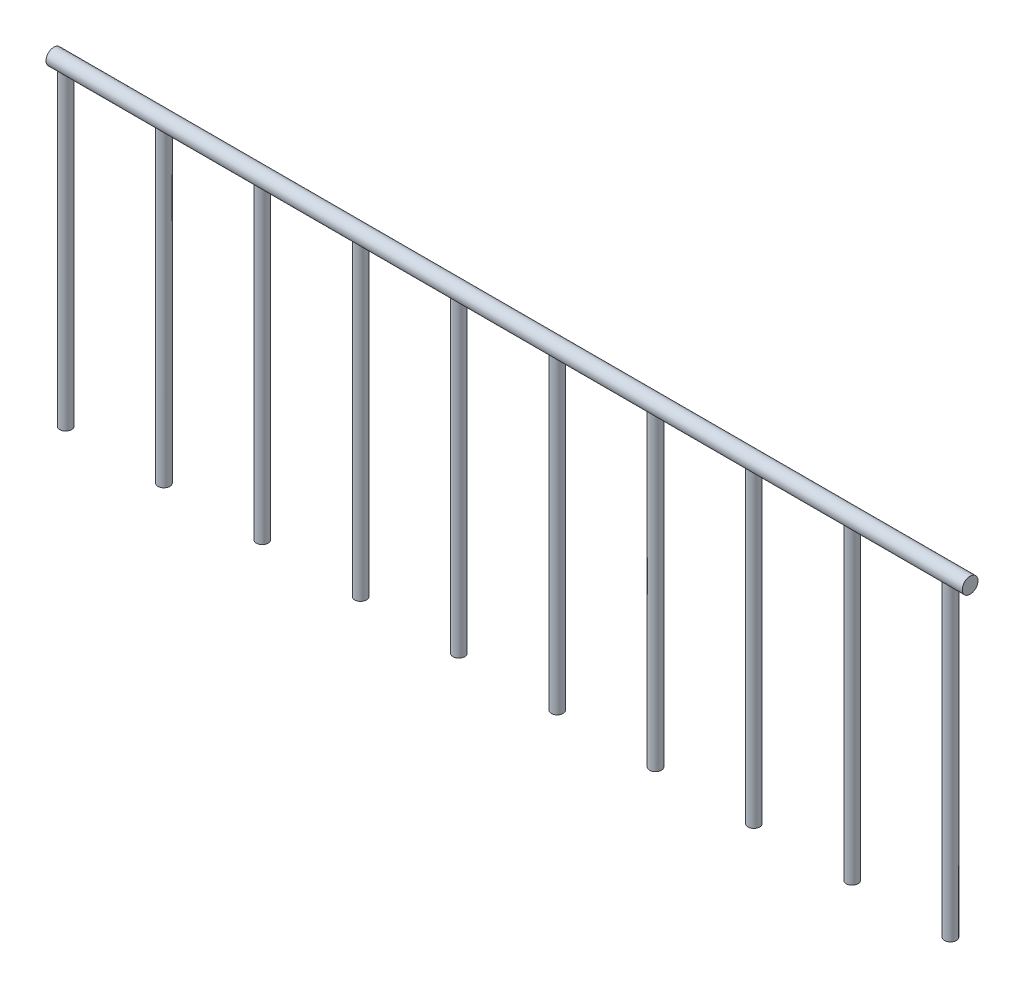
SolidWorks part; units mm, degrees
ref_plane "Front Plane" through (0, 0, 0) normal (0, 0, 1) x (1, 0, 0)
ref_plane "Top Plane" through (0, 0, 0) normal (0, 1, 0) x (1, 0, 0)
ref_plane "Right Plane" through (0, 0, 0) normal (1, 0, 0) x (0, 0, -1)
sketch "Sketch1" plane through (0, 0, 0) normal (0, 1, 0) x (1, 0, 0)
  line L0 (0, 0) -> (25, 0) construction
  circle A0 centre (0, 0) radius 1.5
  circle A1 centre (25, 0) radius 1.5
  circle A2 centre (50, 0) radius 1.5
  circle A3 centre (75, 0) radius 1.5
  circle A4 centre (100, 0) radius 1.5
  circle A5 centre (125, 0) radius 1.5
  circle A6 centre (150, 0) radius 1.5
  circle A7 centre (175, 0) radius 1.5
  circle A8 centre (200, 0) radius 1.5
  circle A9 centre (225, 0) radius 1.5
  dimension "D1" = 3
  dimension "D3" = 25
  dimension "D2" = 10
extrude "Vertical Bars" add sketch "Sketch1" along normal mid plane 80
sketch "Sketch2" plane through (0, 0, 0) normal (1, 0, 0) x (0, 0, -1)
  line L0 (1.5, 40) -> (-1.5, 40) construction
  circle A0 centre (0, 40) radius 2
  point P2 (0, 40)
  point P5 (0, 0)
  point P6 (0, 0)
  dimension "D1" = 4
extrude "Horizontal Bar" add sketch "Sketch2" along normal blind 230 and the other way blind 3
